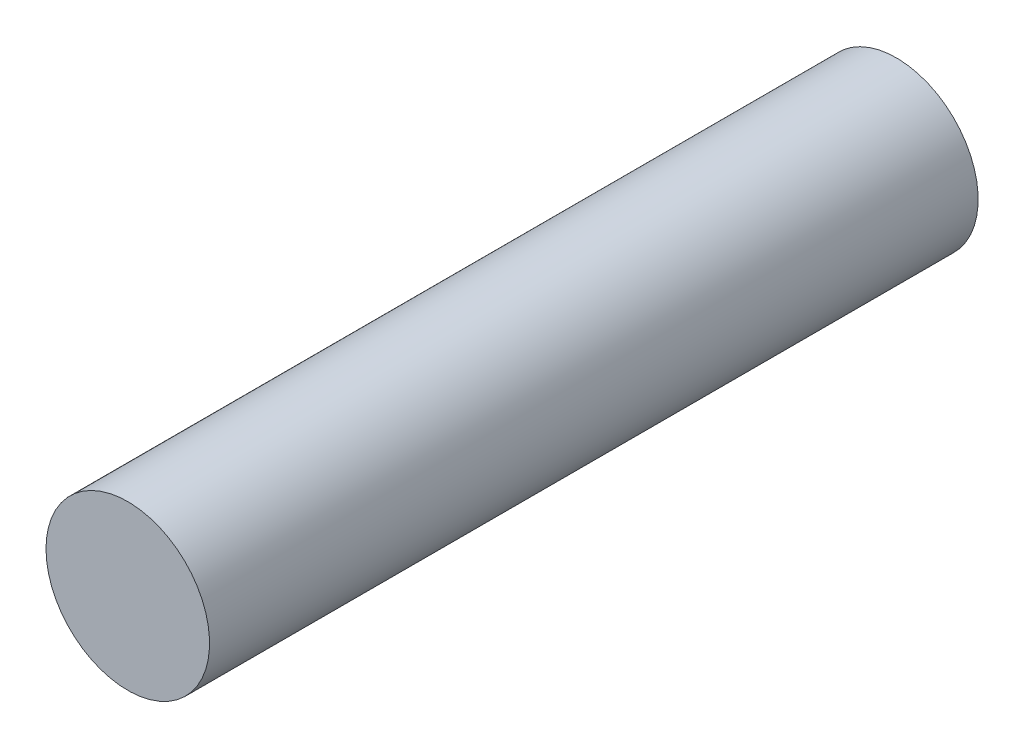
SolidWorks part; units mm, degrees
ref_plane "Front Plane" through (0, 0, 0) normal (0, 0, 1) x (1, 0, 0)
ref_plane "Top Plane" through (0, 0, 0) normal (0, 1, 0) x (1, 0, 0)
ref_plane "Right Plane" through (0, 0, 0) normal (1, 0, 0) x (0, 0, -1)
sketch "Sketch1" plane through (0, 0, 0) normal (0, 0, 1) x (1, 0, 0)
  circle A0 centre (0, 0) radius 3.175
  dimension "D1" = 6.35
extrude "Boss-Extrude1" add sketch "Sketch1" along normal blind 29.845
